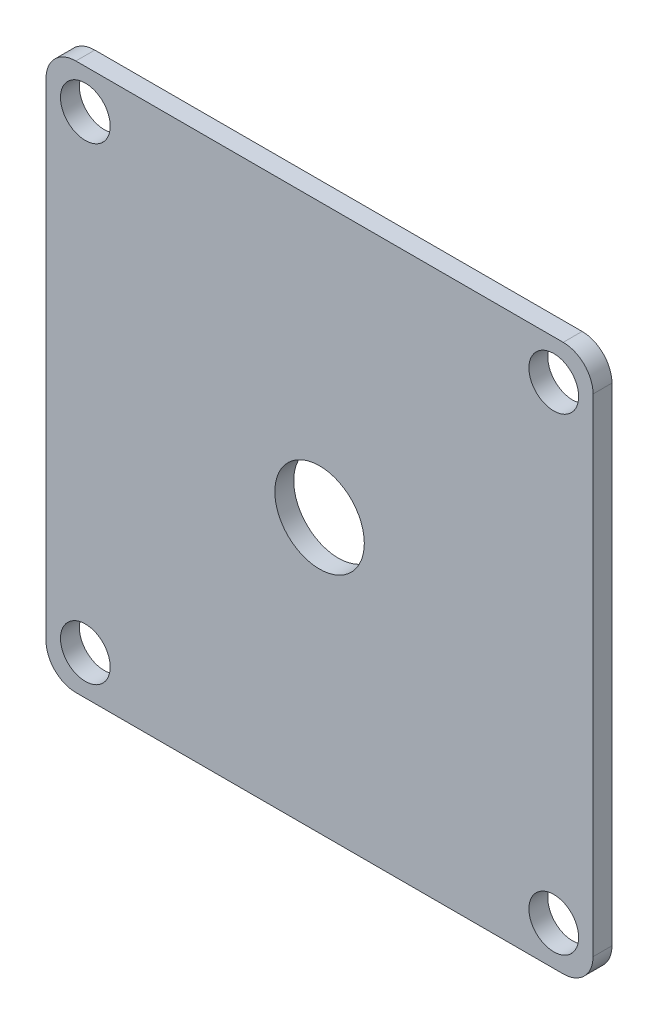
SolidWorks part; units mm, degrees
ref_plane "Спереди" through (0, 0, 0) normal (0, 0, 1) x (1, 0, 0)
ref_plane "Сверху" through (0, 0, 0) normal (0, 1, 0) x (1, 0, 0)
ref_plane "Справа" through (0, 0, 0) normal (1, 0, 0) x (0, 0, -1)
sketch "Эскиз1" plane through (0, 0, 0) normal (0, 0, 1) x (1, 0, 0)
  line L1 (3, 0) -> (52, 0)
  line L2 (0, 3) -> (0, 52)
  line L3 (3, 55) -> (52, 55)
  line L4 (55, 3) -> (55, 52)
  arc A0 (0, 52) -> (3, 55) centre (3, 52) cw
  arc A1 (52, 55) -> (55, 52) centre (52, 52) cw
  arc A2 (52, 0) -> (55, 3) centre (52, 3) ccw
  arc A3 (3, 0) -> (0, 3) centre (3, 3) cw
  point P13 (0, 0)
  dimension "D1" = 3
  dimension "D2" = 55
  dimension "D3" = 55
extrude "Бобышка-Вытянуть1" add sketch "Эскиз1" along normal blind 1.9
sketch "Эскиз2" plane through (0, 0, 1.9) normal (0, 0, 1) x (1, 0, 0)
  line L0 (0, 52) -> (0, 3) construction
  line L1 (3, 0) -> (52, 0) construction
  circle A0 centre (27.5, 27.5) radius 4.5
  point P4 (0, 27.5)
  point P7 (27.5, 0)
  dimension "D1" = 9
  dimension "D2" = 0
  dimension "D3" = 0
extrude "Вырез-Вытянуть1" cut sketch "Эскиз2" against normal through all
sketch "Эскиз3" plane through (0, 0, 1.9) normal (0, 0, 1) x (1, 0, 0)
  circle A0 centre (3.95, 3.95) radius 2.5
  circle A1 centre (27.5, 27.5) radius 4.5 construction
  circle A2 centre (51.05, 3.95) radius 2.5
  circle A3 centre (51.05, 51.05) radius 2.5
  circle A4 centre (3.95, 51.05) radius 2.5
  dimension "D1" = 5
  dimension "D2" = 23.55
  dimension "D3" = 23.55
  dimension "D4" = 2
  dimension "D5" = 2
extrude "Вырез-Вытянуть2" cut sketch "Эскиз3" against normal through all
